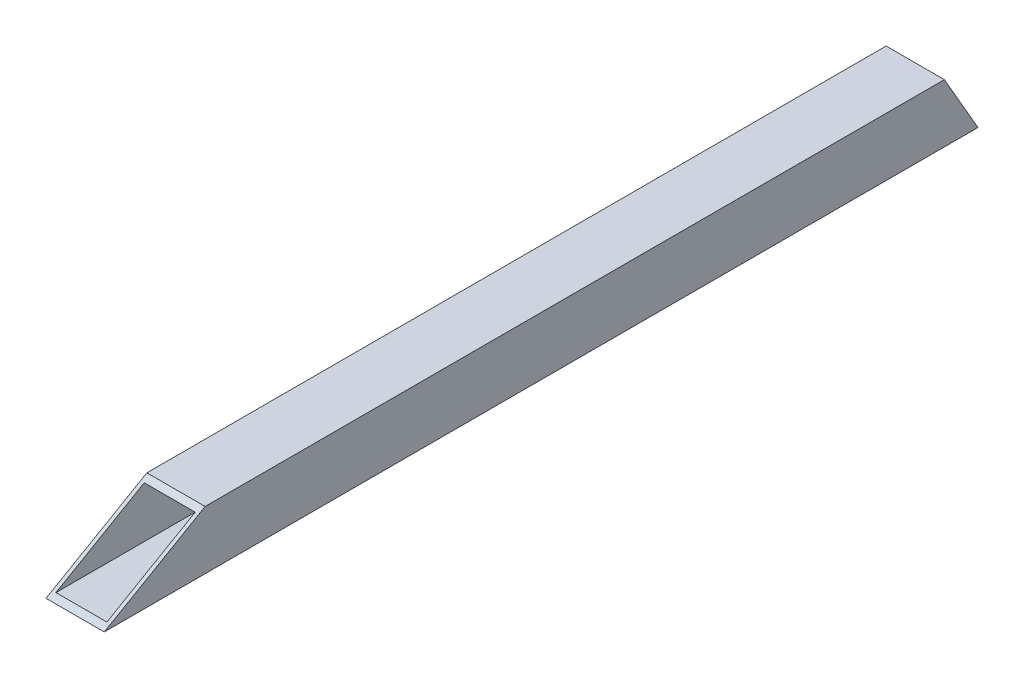
SolidWorks part; units mm, degrees
material "AISI 1020"
ref_plane "Front Plane" through (0, 0, 0) normal (0, 0, 1) x (1, 0, 0)
ref_plane "Top Plane" through (0, 0, 0) normal (0, 1, 0) x (1, 0, 0)
ref_plane "Right Plane" through (0, 0, 0) normal (1, 0, 0) x (0, 0, -1)
sketch "Sketch1" plane through (0, 0, 0) normal (0, 0, 1) x (1, 0, 0)
  line L0 (22.225, 22.225) -> (22.225, 25.4) construction
  line L1 (-25.4, -25.4) -> (25.4, -25.4)
  line L2 (-25.4, -25.4) -> (-25.4, 25.4)
  line L3 (-25.4, 25.4) -> (25.4, 25.4)
  line L4 (25.4, -25.4) -> (25.4, 25.4)
  line L5 (-25.4, -25.4) -> (25.4, 25.4) construction
  line L6 (-25.4, 25.4) -> (25.4, -25.4) construction
  line L7 (-22.225, -22.225) -> (22.225, -22.225)
  line L8 (-22.225, -22.225) -> (-22.225, 22.225)
  line L9 (-22.225, 22.225) -> (22.225, 22.225)
  line L10 (22.225, -22.225) -> (22.225, 22.225)
  line L11 (-22.225, -22.225) -> (22.225, 22.225) construction
  line L12 (-22.225, 22.225) -> (22.225, -22.225) construction
  line L13 (22.225, -22.225) -> (25.4, -22.225) construction
  point P0 (0, 0)
  point P6 (0, 0)
  dimension "D2" = 50.8
  dimension "D3" = 3.175
extrude "Boss-Extrude1" add sketch "Sketch1" along normal blind 762
sketch "Sketch2" plane through (-25.4, 0, 0) normal (-1, 0, 0) x (0, 0, 1)
  line L0 (0, -25.4) -> (29.3294, 25.4)
  line L2 (29.3294, 25.4) -> (0, 25.4)
  line L3 (0, -25.4) -> (0, 25.4)
  line L4 (762, -25.4) -> (674.0118, 25.4)
  line L5 (762, 25.4) -> (0, 25.4) construction
  line L6 (674.0118, 25.4) -> (762, 25.4)
  line L7 (762, 25.4) -> (762, -25.4)
  dimension "D1" = 30
  dimension "D2" = 30
extrude "Cut-Extrude1" cut sketch "Sketch2" against normal through all
